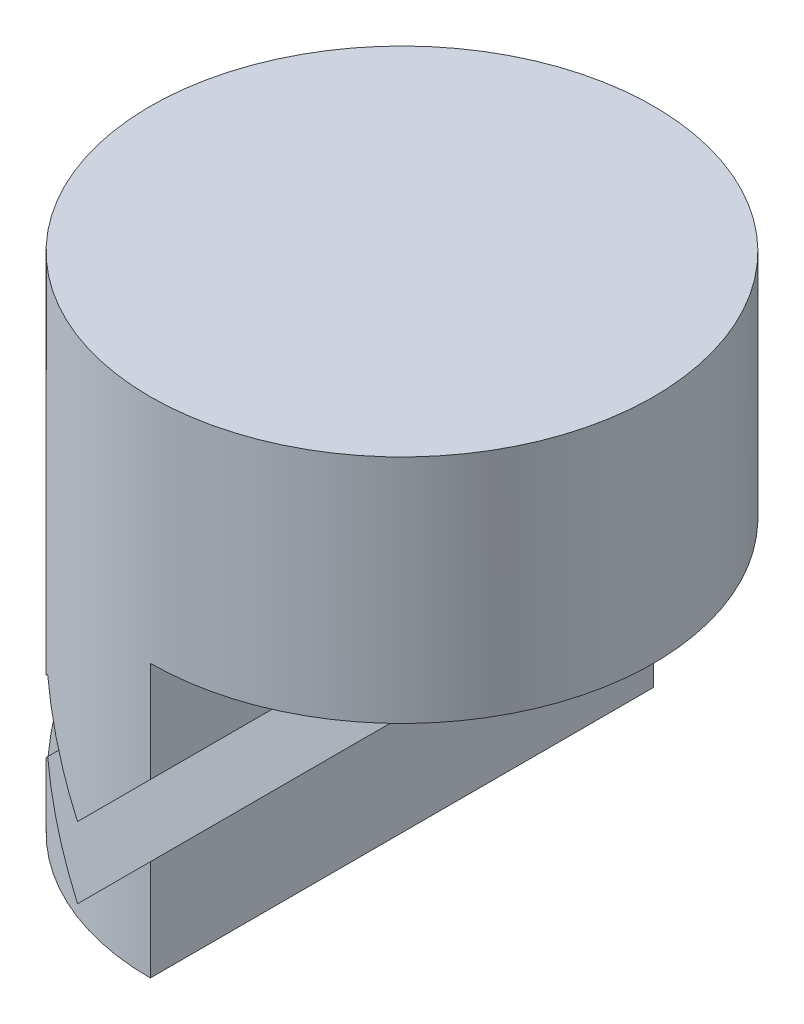
SolidWorks part; units mm, degrees
ref_plane "前视基准面" through (0, 0, 0) normal (0, 0, 1) x (1, 0, 0)
ref_plane "上视基准面" through (0, 0, 0) normal (0, 1, 0) x (1, 0, 0)
ref_plane "右视基准面" through (0, 0, 0) normal (1, 0, 0) x (0, 0, -1)
sketch "草图1" plane through (0, 0, 0) normal (0, 1, 0) x (1, 0, 0)
  circle A0 centre (0, 0) radius 50
  dimension "D1" = 100
extrude "凸台-拉伸1" add sketch "草图1" along normal blind 100
sketch "草图2" plane through (0, 0, 0) normal (0, 0, 1) x (1, 0, 0)
  line L0 (0, 0) -> (0, 20)
  line L1 (-50, 0) -> (50, 0) construction
  line L4 (-17.7012, 16.4409) -> (0, 34.1421)
  line L5 (0, 34.1421) -> (0, 54.1421)
  line L6 (0, 54.1421) -> (63.983, 54.1421)
  line L7 (63.983, 54.1421) -> (63.983, 0)
  line L8 (63.983, 0) -> (0, 0)
  line L11 (-31.8198, 16.4645) -> (-17.6777, 2.3223)
  line L13 (0, 20) -> (-17.6777, 2.3223)
  line L14 (-31.8198, 16.4645) -> (-38.8909, 9.3934)
  line L15 (-38.8909, 9.3934) -> (-45.9619, 16.4645)
  line L16 (-45.9619, 16.4645) -> (-31.8433, 30.5831)
  line L18 (-17.7012, 16.4409) -> (-31.8433, 30.5831)
  dimension "D1" = 25
  dimension "D2" = 20
  dimension "D3" = 20
  dimension "D4" = 10
  dimension "D5" = 20
  dimension "D6" = 10
  dimension "D7" = 10
extrude "切除-拉伸1" cut sketch "草图2" against normal through all both and the other way through all
